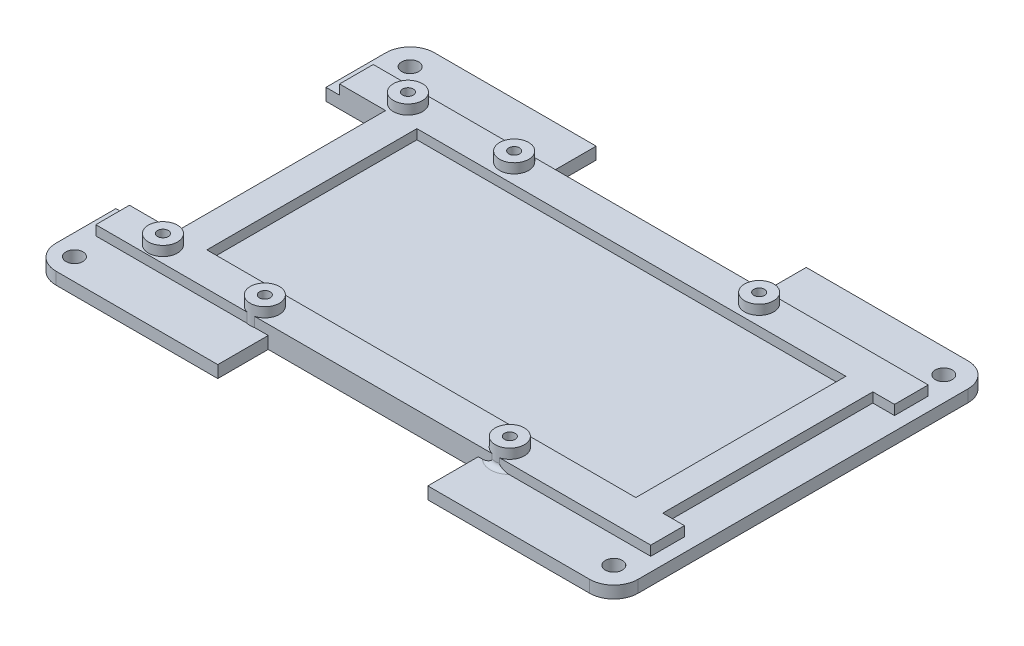
SolidWorks part; units mm, degrees
ref_plane "Přední" through (0, 0, 0) normal (0, 0, 1) x (1, 0, 0)
ref_plane "Horní" through (0, 0, 0) normal (0, 1, 0) x (1, 0, 0)
ref_plane "Pravá" through (0, 0, 0) normal (1, 0, 0) x (0, 0, -1)
sketch "Skica1" plane through (0, -39.4, 0) normal (0, -1, 0) x (1, 0, 0)
  line L0 (-4.318, -71.206) -> (-4.318, -3.206)
  line L1 (0.682, 1.794) -> (110.682, 1.794)
  line L3 (115.682, -3.206) -> (115.682, -71.206)
  line L4 (110.682, -76.206) -> (0.682, -76.206)
  arc A3 (0.682, 1.794) -> (-4.318, -3.206) centre (0.682, -3.206) ccw construction
  arc A4 (115.682, -3.206) -> (110.682, 1.794) centre (110.682, -3.206) ccw construction
  arc A5 (110.682, -76.206) -> (115.682, -71.206) centre (110.682, -71.206) ccw construction
  arc A7 (-4.318, -71.206) -> (0.682, -76.206) centre (0.682, -71.206) ccw construction
  arc A8 (0.682, 1.794) -> (-4.318, -3.206) centre (0.682, -3.206) ccw
  arc A9 (115.682, -3.206) -> (110.682, 1.794) centre (110.682, -3.206) ccw
  arc A10 (110.682, -76.206) -> (115.682, -71.206) centre (110.682, -71.206) ccw
  arc A11 (-4.318, -71.206) -> (0.682, -76.206) centre (0.682, -71.206) ccw
extrude "Přidat vysunutím1" add sketch "Skica1" against normal blind 2.5
sketch "Skica2" plane through (0, -36.9, 0) normal (0, 1, 0) x (1, 0, 0)
  line L1 (77.332, 8.606) -> (34.032, 8.606)
  line L2 (77.332, 8.606) -> (77.332, -1.794)
  line L3 (77.332, -1.794) -> (34.032, -1.794)
  line L4 (34.032, 8.606) -> (34.032, -1.794)
  line L6 (6.082, 15.556) -> (-4.318, 15.556)
  line L7 (6.082, 15.556) -> (6.082, 58.856)
  line L8 (6.082, 58.856) -> (-4.318, 58.856)
  line L9 (-4.318, 15.556) -> (-4.318, 58.856)
  line L11 (77.332, 65.806) -> (34.032, 65.806)
  line L12 (77.332, 65.806) -> (77.332, 76.206)
  line L13 (77.332, 76.206) -> (34.032, 76.206)
  line L14 (34.032, 65.806) -> (34.032, 76.206)
  line L15 (115.682, 37.206) -> (6.082, 37.206) construction
  line L17 (77.232, 8.506) -> (34.132, 8.506) construction
  line L18 (34.132, 8.506) -> (34.132, 0.706) construction
  line L19 (77.232, 0.706) -> (77.232, 8.506) construction
  line L20 (110.682, -1.794) -> (0.682, -1.794) construction
  line L21 (-4.318, 3.206) -> (-4.318, 71.206) construction
  line L22 (0.682, 76.206) -> (110.682, 76.206) construction
  line L23 (115.682, 71.206) -> (115.682, 3.206) construction
  dimension "D1" = 0.1
  dimension "D2" = 0.1
  dimension "D3" = 0.1
extrude "Odebrat vysunutím1" cut sketch "Skica2" against normal through all
sketch "Skica6" plane through (0, -36.9, 0) normal (0, 1, 0) x (1, 0, 0)
  line L0 (77.332, 8.606) -> (34.032, 8.606) construction
  line L1 (-4.318, 15.556) -> (115.682, 15.556)
  line L2 (-4.318, 15.556) -> (-4.318, 8.606)
  line L3 (-4.318, 8.606) -> (115.682, 8.606)
  line L4 (115.682, 15.556) -> (115.682, 8.606)
  line L5 (34.032, 65.806) -> (77.332, 65.806) construction
  line L6 (-4.318, 58.856) -> (115.682, 58.856)
  line L7 (-4.318, 58.856) -> (-4.318, 65.806)
  line L8 (-4.318, 65.806) -> (115.682, 65.806)
  line L9 (115.682, 58.856) -> (115.682, 65.806)
  line L10 (115.682, 71.206) -> (115.682, 3.206) construction
extrude "Přidat vysunutím3" add sketch "Skica6" along normal blind 2
sketch "Skica7" plane through (0, -36.9, 0) normal (0, 1, 0) x (1, 0, 0)
  line L0 (-4.318, 8.606) -> (115.682, 8.606) construction
  line L1 (108.4105, 8.606) -> (102.8559, 8.606)
  line L2 (108.4105, 8.606) -> (108.4105, 65.806)
  line L3 (108.4105, 65.806) -> (102.8559, 65.806)
  line L4 (102.8559, 8.606) -> (102.8559, 65.806)
  line L5 (115.682, 65.806) -> (77.332, 65.806) construction
  line L6 (-4.318, 8.606) -> (34.032, 8.606) construction
  line L7 (7.983, 8.606) -> (14.4264, 8.606)
  line L8 (7.983, 8.606) -> (7.983, 65.806)
  line L9 (7.983, 65.806) -> (14.4264, 65.806)
  line L10 (14.4264, 8.606) -> (14.4264, 65.806)
  line L11 (34.032, 65.806) -> (-4.318, 65.806) construction
extrude "Přidat vysunutím4" add sketch "Skica7" along normal blind 2
sketch "Skica3" plane through (0, -36.9, 0) normal (0, 1, 0) x (1, 0, 0)
  circle A0 centre (30.432, 11.506) radius 3
  circle A1 centre (8.982, 11.956) radius 3
  circle A2 centre (8.982, 62.456) radius 3
  circle A3 centre (30.432, 62.906) radius 3
  circle A4 centre (80.932, 62.906) radius 3
  circle A5 centre (80.932, 11.506) radius 3
  dimension "D1" = 6
extrude "Přidat vysunutím2" add sketch "Skica3" along normal blind 4
hole_wizard "Ø2.2 (2.2) průměr díry1" positions "Skica5" profile "Skica4" hole size "Ø2.2" standard "DIN"
sketch "Skica5" plane through (0, -39.4, 0) normal (0, -1, 0) x (-1, 0, 0)
  point P0 (-8.982, 62.456)
  point P3 (-30.432, 62.906)
  point P6 (-80.932, 62.906)
  point P9 (-80.932, 11.506)
  point P12 (-30.432, 11.506)
  point P16 (-8.982, 11.956)
sketch "Skica4" plane through (8.982, -39.4, -62.456) normal (1, 0, 0) x (0, 0, -1)
  line L0 (0, 0) -> (0, 10)
  line L1 (0, 10) -> (1.1, 10)
  line L2 (1.1, 10) -> (1.1, 0)
  line L5 (1.1, 0) -> (0, 0)
  line L10 (0, 10) -> (-1.1, 10) construction
  line L11 (0, -6.35) -> (0, 107.95) construction
  dimension "Průměr díry" = 2.2
  dimension "Hloubka díry" = 10
  dimension "Úhel vrtání" = 180
fillet "Zaoblit1" radius 1 3 edges at (80.932, -36.9, -8.506) (80.932, -36.9, -65.906) (30.432, -36.9, -65.906)
ref_plane "Rovina1" through (0, 0, -37.206) normal (0, 0, 1) x (1, 0, 0)
ref_plane "Rovina2" through (55.682, 0, 0) normal (1, 0, 0) x (0, 0, -1)
sketch "Skica8" plane through (0, -36.9, 0) normal (0, 1, 0) x (1, 0, 0)
  line L0 (27.677, 65.806) -> (-4.318, 65.806) construction
  line L1 (-4.318, 8.606) -> (-1.518, 8.606)
  line L2 (-4.318, 8.606) -> (-4.318, 65.806)
  line L3 (-4.318, 65.806) -> (-1.518, 65.806)
  line L4 (-1.518, 8.606) -> (-1.518, 65.806)
  line L5 (115.682, 65.806) -> (83.687, 65.806) construction
  line L6 (115.682, 8.606) -> (112.882, 8.606)
  line L7 (115.682, 8.606) -> (115.682, 65.806)
  line L8 (115.682, 65.806) -> (112.882, 65.806)
  line L9 (112.882, 8.606) -> (112.882, 65.806)
  dimension "D1" = 2.8
extrude "Odebrat vysunutím3" cut sketch "Skica8" along normal through all
hole_wizard "Ø3.5 (3.5) průměr díry1" positions "Skica10" profile "Skica9" hole size "Ø3.5" standard "DIN"
sketch "Skica10" plane through (0, -39.4, 0) normal (0, -1, 0) x (-1, 0, 0)
  point P0 (0, 2.6965)
  point P2 (-0.682, 71.206)
  point P5 (-110.682, 71.206)
  point P8 (-110.682, 3.206)
sketch "Skica9" plane through (0, -39.4, -2.6965) normal (1, 0, 0) x (0, 0, -1)
  line L0 (0, 0) -> (0, 10)
  line L1 (0, 10) -> (1.75, 10)
  line L2 (1.75, 10) -> (1.75, 0)
  line L5 (1.75, 0) -> (0, 0)
  line L10 (0, 10) -> (-1.75, 10) construction
  line L11 (0, -6.35) -> (0, 107.95) construction
  dimension "Průměr díry" = 3.5
  dimension "Hloubka díry" = 10
  dimension "Úhel vrtání" = 180
